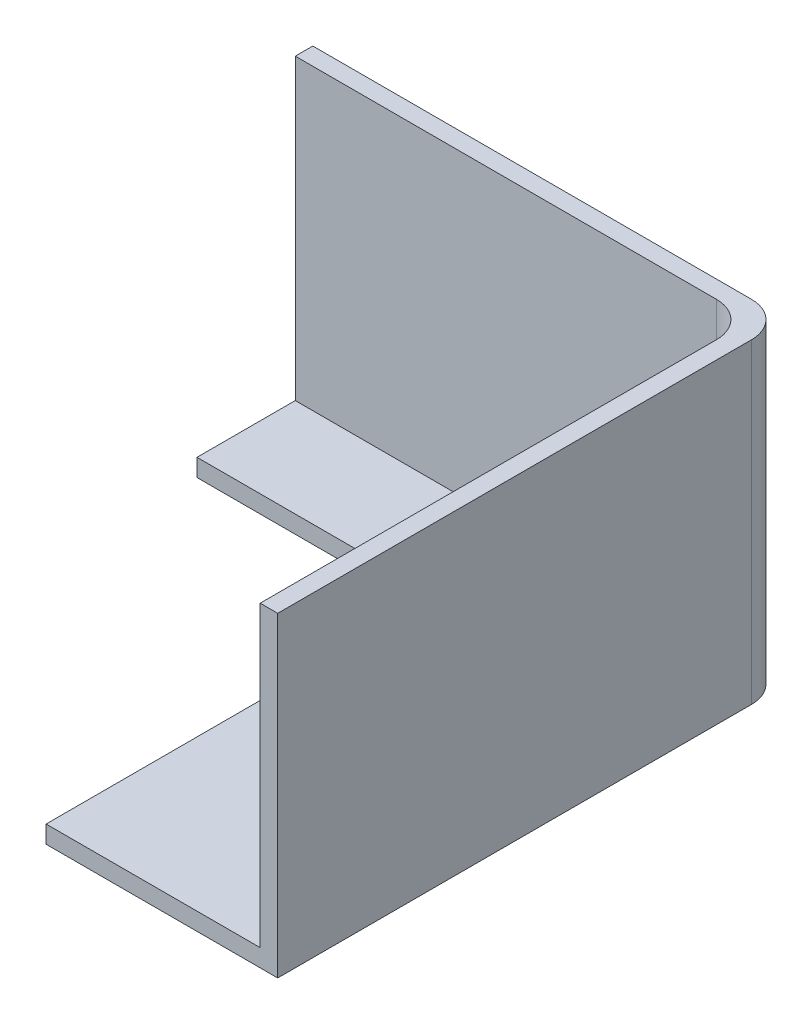
SolidWorks part; units mm, degrees
ref_plane "前视基准面" through (0, 0, 0) normal (0, 0, 1) x (1, 0, 0)
ref_plane "上视基准面" through (0, 0, 0) normal (0, 1, 0) x (1, 0, 0)
ref_plane "右视基准面" through (0, 0, 0) normal (1, 0, 0) x (0, 0, -1)
other "Configuration Table"
sketch "草图1" plane through (0, 0, 0) normal (0, 1, 0) x (1, 0, 0)
  line L1 (0, 0) -> (135, 0)
  line L2 (0, 0) -> (0, -145)
  line L3 (0, -145) -> (135, -145)
  line L4 (135, 0) -> (135, -145)
  dimension "D1" = 135
  dimension "D2" = 145
extrude "凸台-拉伸1" add sketch "草图1" along normal blind 90
sketch "草图2" plane through (0, 90, 0) normal (0, 1, 0) x (1, 0, 0)
  line L0 (0, 0) -> (0, -145) construction
  line L1 (0, -5) -> (130, -5)
  line L2 (0, -5) -> (0, -145)
  line L3 (0, -145) -> (130, -145)
  line L4 (130, -5) -> (130, -145)
  line L5 (0, -145) -> (135, -145) construction
  line L6 (135, 0) -> (0, 0) construction
  line L7 (135, -145) -> (135, 0) construction
  dimension "D1" = 5
  dimension "D2" = 5
extrude "切除-拉伸1" cut sketch "草图2" against normal offset from surface (85 mm away) 5 up to face at (67.5, 0, 72.5)
sketch "草图3" plane through (0, 5, 0) normal (0, 1, 0) x (1, 0, 0)
  line L0 (0, -145) -> (0, -5) construction
  line L1 (0, -33) -> (69, -33)
  line L2 (0, -33) -> (0, -145)
  line L3 (0, -145) -> (69, -145)
  line L4 (69, -33) -> (69, -145)
  line L5 (130, -145) -> (0, -145) construction
  dimension "D1" = 69
  dimension "D2" = 112
extrude "切除-拉伸2" cut sketch "草图3" against normal up to surface (5 mm away) up to face at (67.5, 0, 72.5)
sketch "草图4" plane through (0, 5, 0) normal (0, 1, 0) x (1, 0, 0)
  line L0 (0, -33) -> (0, -5) construction
  line L1 (130, -145) -> (69, -145) construction
  circle A0 centre (64, -23) radius 1.4
  dimension "D1" = 2.8
  dimension "D2" = 64
  dimension "D3" = 122
extrude "切除-拉伸3" cut sketch "草图4" against normal up to surface (5 mm away) up to face at (68, 0, 59.3333)
fillet "圆角1" radius 10 3 edges at (69, 2.5, 33) (135, 45, 0) (130, 47.5, 5)
